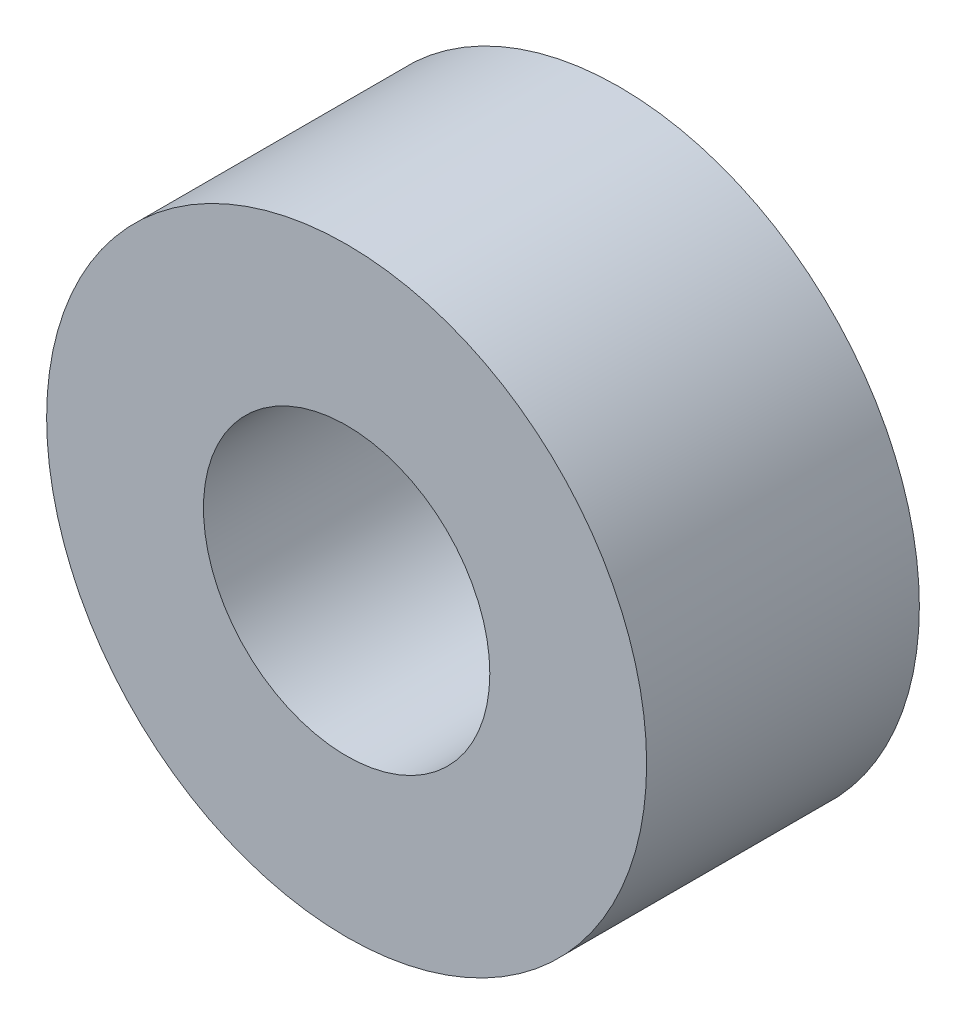
SolidWorks part; units mm, degrees
ref_plane "Ebene vorne" through (0, 0, 0) normal (0, 0, 1) x (1, 0, 0)
ref_plane "Ebene oben" through (0, 0, 0) normal (0, 1, 0) x (1, 0, 0)
ref_plane "Ebene rechts" through (0, 0, 0) normal (1, 0, 0) x (0, 0, -1)
sketch "Skizze1" plane through (0, 0, 0) normal (0, 0, 1) x (1, 0, 0)
  circle A0 centre (0, 0) radius 4.4
  dimension "D1" = 8.8
extrude "Aufsatz-Linear austragen1" add sketch "Skizze1" along normal blind 4
hole_wizard "M5 Gewindebohrung1" positions "Skizze2" profile "Skizze3" tap size "M5" standard "DIN" end condition up to next
sketch "Skizze2" plane through (0, 0, 4) normal (0, 0, 1) x (1, 0, 0)
  point P0 (0, 0)
sketch "Skizze3" plane through (0, 0, 4) normal (1, 0, 0) x (0, -1, 0)
  line L0 (0, 0) -> (0, 4)
  line L1 (0, 4) -> (2.1, 4)
  line L2 (2.1, 4) -> (2.1, 0)
  line L5 (2.1, 0) -> (0, 0)
  line L11 (0, -6.35) -> (0, 107.95) construction
  dimension "Bohrerdurchmesser" = 4.2
  dimension "Bohrungstiefe" = 4
cosmetic thread "Bohrungsgewinde1" parameters "D2"=5
